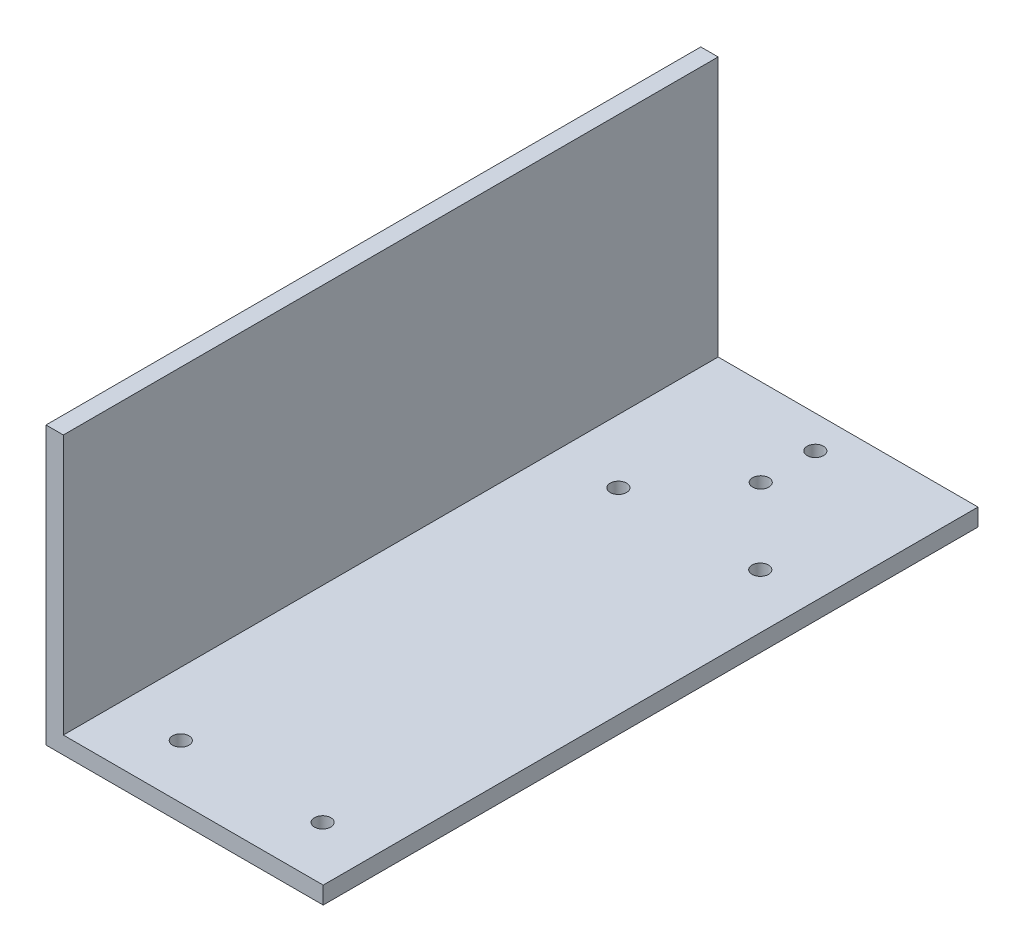
SolidWorks part; units mm, degrees
ref_plane "Front Plane" through (0, 0, 0) normal (0, 0, 1) x (1, 0, 0)
ref_plane "Top Plane" through (0, 0, 0) normal (0, 1, 0) x (1, 0, 0)
ref_plane "Right Plane" through (0, 0, 0) normal (1, 0, 0) x (0, 0, -1)
sketch "Croquis1" plane through (0, 0, 0) normal (0, 0, 1) x (1, 0, 0)
  line L1 (0, 0) -> (50.8, 0)
  line L2 (0, 0) -> (0, 50.8)
  line L3 (0, 50.8) -> (3.175, 50.8)
  line L4 (50.8, 0) -> (50.8, 3.175)
  line L7 (50.8, 3.175) -> (3.175, 3.175)
  line L8 (3.175, 50.8) -> (3.175, 3.175)
  dimension "D1" = 50.8
  dimension "D2" = 50.8
  dimension "D3" = 3.175
  dimension "D4" = 3.175
extrude "Saliente-Extruir1" add sketch "Croquis1" along normal blind 120
sketch "Croquis2" plane through (0, 3.175, 0) normal (0, 1, 0) x (1, 0, 0)
  line L1 (50.8, -120) -> (50.8, 0) construction
  line L4 (50.8, -120) -> (3.175, -120) construction
  circle A0 centre (40.8, -29.9) radius 1.5
  circle A1 centre (14.8, -29.9) radius 1.5
  circle A2 centre (40.8, -110.1) radius 1.5
  circle A3 centre (14.8, -110.1) radius 1.5
  dimension "D1" = 26
  dimension "D2" = 10
  dimension "D3" = 80.2
  dimension "D4" = 26
  dimension "D5" = 0
  dimension "D6" = 0
  dimension "D7" = 9.9
extrude "Cortar-Extruir1" cut sketch "Croquis2" against normal blind 100
sketch "Croquis3" plane through (0, 3.175, 0) normal (0, 1, 0) x (1, 0, 0)
  line L0 (50.8, 0) -> (3.175, 0) construction
  line L3 (50.8, -120) -> (50.8, 0) construction
  circle A0 centre (26.985, -6) radius 1.5
  circle A3 centre (26.985, -16) radius 1.5
  dimension "D1" = 10
  dimension "D2" = 6
  dimension "D3" = 23.815
extrude "Cortar-Extruir2" cut sketch "Croquis3" against normal blind 100
